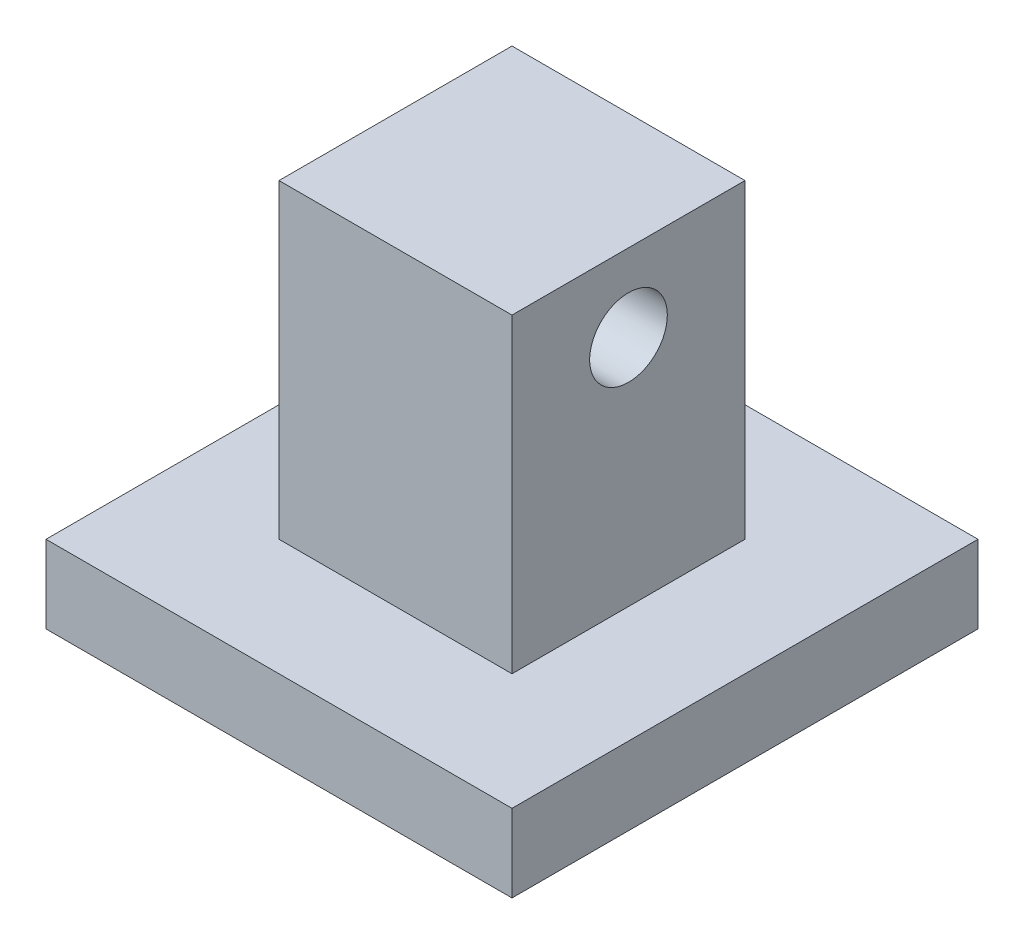
SolidWorks part; units mm, degrees
ref_plane "Front Plane" through (0, 0, 0) normal (0, 0, 1) x (1, 0, 0)
ref_plane "Top Plane" through (0, 0, 0) normal (0, 1, 0) x (1, 0, 0)
ref_plane "Right Plane" through (0, 0, 0) normal (1, 0, 0) x (0, 0, -1)
sketch "Sketch1" plane through (0, 0, 0) normal (0, 1, 0) x (1, 0, 0)
  line L1 (-76.2, 76.2) -> (76.2, 76.2)
  line L2 (-76.2, 76.2) -> (-76.2, -76.2)
  line L3 (-76.2, -76.2) -> (76.2, -76.2)
  line L4 (76.2, 76.2) -> (76.2, -76.2)
  line L5 (-76.2, 76.2) -> (76.2, -76.2) construction
  line L6 (-76.2, -76.2) -> (76.2, 76.2) construction
  point P0 (0, 0)
  dimension "D1" = 152.4
  dimension "D2" = 152.4
extrude "Boss-Extrude1" add sketch "Sketch1" along normal blind 25.4
sketch "Sketch2" plane through (0, 25.4, 0) normal (0, 1, 0) x (1, 0, 0)
  line L1 (-38.1, -38.1) -> (38.1, -38.1)
  line L2 (-38.1, -38.1) -> (-38.1, 38.1)
  line L3 (-38.1, 38.1) -> (38.1, 38.1)
  line L4 (38.1, -38.1) -> (38.1, 38.1)
  line L5 (-38.1, -38.1) -> (38.1, 38.1) construction
  line L6 (-38.1, 38.1) -> (38.1, -38.1) construction
  point P0 (0, 0)
  dimension "D1" = 76.2
  dimension "D2" = 76.2
extrude "Boss-Extrude2" add sketch "Sketch2" along normal blind 101.6
sketch "Sketch3" plane through (38.1, 0, 0) normal (1, 0, 0) x (0, 0, -1)
  line L0 (-38.1, 127) -> (38.1, 127) construction
  circle A0 centre (0, 101.6) radius 12.7
  dimension "D1" = 25.4
extrude "Cut-Extrude1" cut sketch "Sketch3" against normal up to next
